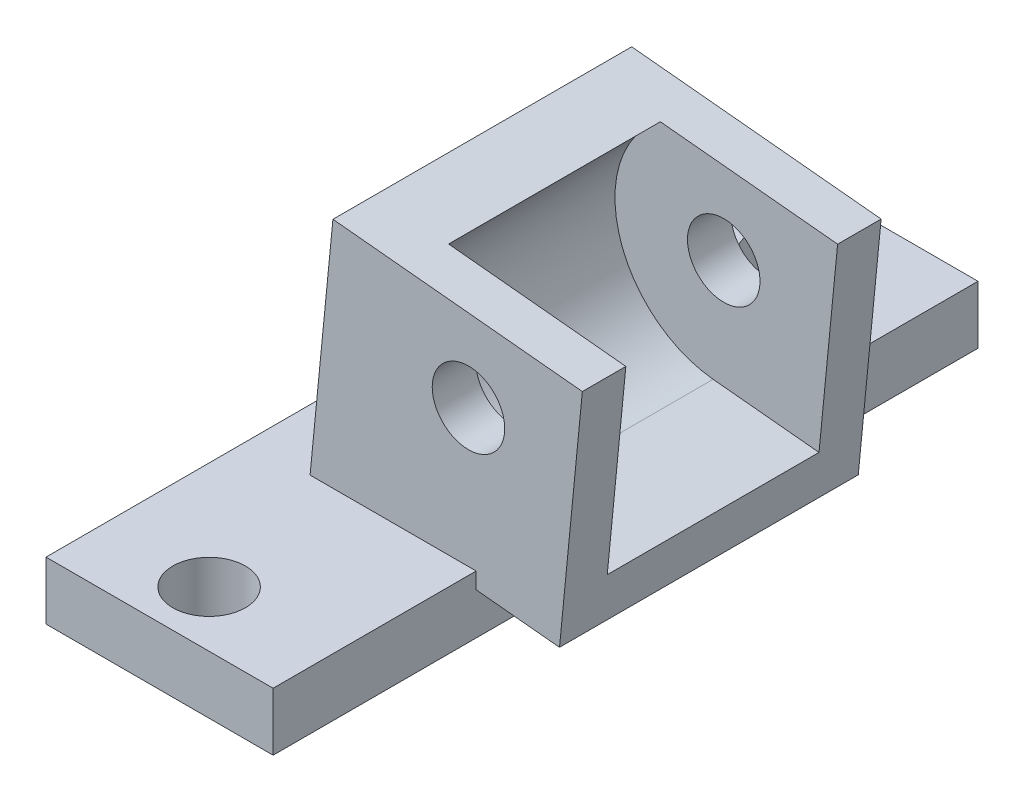
SolidWorks part; units mm, degrees
ref_plane "Front Plane" through (0, 0, 0) normal (0, 0, 1) x (1, 0, 0)
ref_plane "Top Plane" through (0, 0, 0) normal (0, 1, 0) x (1, 0, 0)
ref_plane "Right Plane" through (0, 0, 0) normal (1, 0, 0) x (0, 0, -1)
sketch "Sketch1" plane through (0, 0, 0) normal (0, 0, 1) x (1, 0, 0)
  line L0 (-474.3837, 157.2193) -> (-476.3844, 136.8193)
  line L1 (-489.9044, 158.7414) -> (-462.6347, 156.067) construction
  line L2 (-476.3844, 136.8193) -> (-498.2247, 138.9613)
  line L3 (-498.2247, 138.9613) -> (-496.224, 159.3612)
  line L4 (-496.224, 159.3612) -> (-474.3837, 157.2193)
  line L5 (-491.3026, 144.4842) -> (-462.6347, 141.6727) construction
  line L6 (-485.2846, 141.5205) -> (-469.8952, 140.0112) construction
  line L7 (-485.2846, 141.5205) -> (-469.8952, 140.0112)
  arc A0 (-489.9044, 158.7414) -> (-491.3026, 144.4842) centre (-484.3549, 151) ccw construction
  arc A1 (-491.3026, 144.4842) -> (-485.2846, 141.5205) centre (-484.3549, 151) ccw construction
  arc A2 (-489.9044, 158.7414) -> (-491.3026, 144.4842) centre (-484.3549, 151) ccw
  arc A3 (-491.3026, 144.4842) -> (-485.2846, 141.5205) centre (-484.3549, 151) ccw
  dimension "D1" = 6.35
  dimension "D2" = 3.81
extrude "Boss-Extrude1" add sketch "Sketch1" against normal blind 22.352 contours A3 A2 L4 L3 L2 L0 L7
sketch "Sketch2" plane through (0, 0, -22.352) normal (0, 0, -1) x (-1, 0, 0)
  line L0 (485.2846, 141.5205) -> (476.0125, 140.6111)
  line L1 (476.0125, 140.6111) -> (474.3837, 157.2193)
  line L2 (489.9044, 158.7414) -> (465.5643, 156.3543) construction
  line L3 (474.3837, 157.2193) -> (489.9044, 158.7414)
  arc A0 (485.2846, 141.5205) -> (489.9044, 158.7414) centre (484.3549, 151) ccw
  circle A1 centre (484.3549, 151) radius 3.175 construction
  circle A2 centre (484.3549, 151) radius 3.175
  circle A3 centre (484.3549, 151) radius 3.175
  arc M6 (489.9044, 158.7414) -> (485.2846, 141.5205) centre (484.3549, 151) cw
  line M7 (485.2846, 141.5205) -> (476.0125, 140.6111)
extrude "Boss-Extrude2" add sketch "Sketch2" against normal blind 3.81 contours L3 L1 A2 M7 M6
sketch "Sketch3" plane through (0, 0, 0) normal (0, 0, 1) x (1, 0, 0)
  line L0 (-496.224, 159.3612) -> (-498.2247, 138.9613)
  line L1 (-498.2247, 138.9613) -> (-476.3844, 136.8193)
  line L2 (-476.3844, 136.8193) -> (-474.3837, 157.2193)
  line L3 (-474.3837, 157.2193) -> (-489.9044, 158.7414) construction
  line L4 (-476.0125, 140.6111) -> (-474.3837, 157.2193) construction
  line L5 (-474.3837, 157.2193) -> (-496.224, 159.3612)
  circle A0 centre (-484.3549, 151) radius 3.175 construction
  circle A1 centre (-484.3549, 151) radius 3.175
  circle A2 centre (-484.3549, 151) radius 3.175
  arc M5 (-485.2846, 141.5205) -> (-489.9044, 158.7414) centre (-484.3549, 151) cw
  line M6 (-489.9044, 158.7414) -> (-496.224, 159.3612)
  line M7 (-496.224, 159.3612) -> (-498.2247, 138.9613)
  line M8 (-498.2247, 138.9613) -> (-476.3844, 136.8193)
  line M9 (-476.3844, 136.8193) -> (-476.0125, 140.6111)
  line M10 (-476.0125, 140.6111) -> (-485.2846, 141.5205)
extrude "Boss-Extrude4" add sketch "Sketch3" along normal blind 3.81 contours L2 L5 A1 M5 M10 | M10 M5 M6 M7 M8 M9
ref_plane "Plane1" through (0, 138.9613, 0) normal (0, 1, 0) x (1, 0, 0)
sketch "Sketch4" plane through (0, 138.9613, 0) normal (0, 1, 0) x (1, 0, 0)
  line L1 (-503.5677, 40.132) -> (-483.6809, 40.132)
  line L2 (-503.5677, 40.132) -> (-503.5677, -21.59)
  line L3 (-503.5677, -21.59) -> (-483.6809, -21.59)
  line L4 (-483.6809, 40.132) -> (-483.6809, -21.59)
  dimension "D1" = 17.78
  dimension "D2" = 17.78
extrude "Boss-Extrude5" add sketch "Sketch4" against normal blind 5.08
sketch "Sketch6" plane through (0, 138.9613, 0) normal (0, 1, 0) x (1, 0, 0)
  line L0 (-503.5677, 40.132) -> (-503.5677, -21.59) construction
  circle A0 centre (-494.1697, -16.7052) radius 3.175
  circle A1 centre (-494.1697, 33.8362) radius 3.1126
  dimension "D1" = 9.398
  dimension "D2" = 9.398
extrude "Cut-Extrude2" cut sketch "Sketch6" against normal blind 5.08 contours A0 | A1
